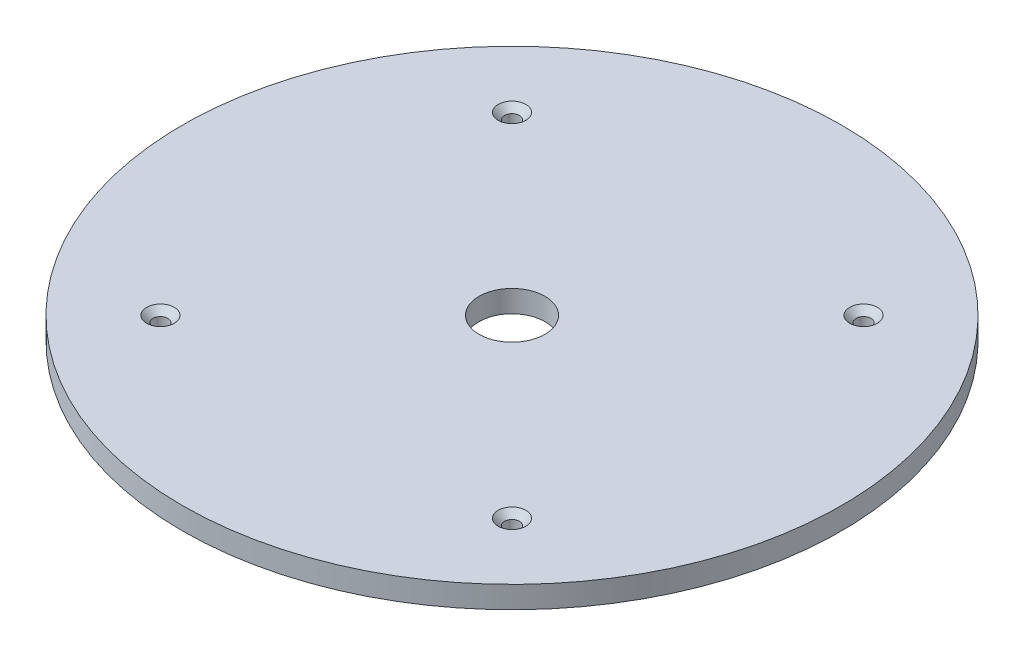
SolidWorks part; units mm, degrees
material "Alumina"
ref_plane "Front Plane" through (0, 0, 0) normal (0, 0, 1) x (1, 0, 0)
ref_plane "Top Plane" through (0, 0, 0) normal (0, 1, 0) x (1, 0, 0)
ref_plane "Right Plane" through (0, 0, 0) normal (1, 0, 0) x (0, 0, -1)
sketch "Sketch1" plane through (0, 0, 0) normal (0, 1, 0) x (1, 0, 0)
  circle A0 centre (0, 0) radius 75
  dimension "D1" = 150
extrude "Boss-Extrude1" add sketch "Sketch1" along normal blind 5
hole_wizard "CSK for M3 Countersunk Flat Head Screw1" positions "Sketch3" profile "Sketch4" countersink size "M3" standard "DIN" end condition through all
sketch "Sketch3" plane through (0, 5, 0) normal (0, 1, 0) x (1, 0, 0)
  point P0 (-40, 40)
  point P8 (40, 40)
  point P9 (40, -40)
  point P10 (-40, -40)
  dimension "D3" = 80
  dimension "D4" = 80
  dimension "D5" = 40
  dimension "D6" = 40
  dimension "D1" = 2
  dimension "D2" = 2
sketch "Sketch4" plane through (-40, 5, -40) normal (1, 0, 0) x (0, 0, 1)
  line L0 (0, 0) -> (0, 5)
  line L1 (0, 5) -> (1.7, 5)
  line L2 (1.7, 5) -> (1.7, 1.45)
  line L3 (1.7, 1.45) -> (3.15, 0)
  line L5 (3.15, 0) -> (0, 0)
  line L6 (-1.7, 1.45) -> (-3.15, 0) construction
  line L11 (0, -6.35) -> (0, 107.95) construction
  dimension "Thru Hole Dia." = 3.4
  dimension "Thru Hole Depth" = 5
  dimension "Near C'Sink Dia." = 6.3
  dimension "Near C'Sink Angle" = 90
sketch "Sketch5" plane through (0, 5, 0) normal (0, 1, 0) x (1, 0, 0)
  circle A0 centre (0, 0) radius 7.5
  dimension "D1" = 15
extrude "Cut-Extrude1" cut sketch "Sketch5" against normal through all
equation "\"Plate Diameter\"= 150mm"
equation "\"Plate Thickness\"= 5mm"
equation "\"D1@Sketch1\"=\"Plate Diameter\""
equation "\"D1@Boss-Extrude1\"=\"Plate Thickness\""
